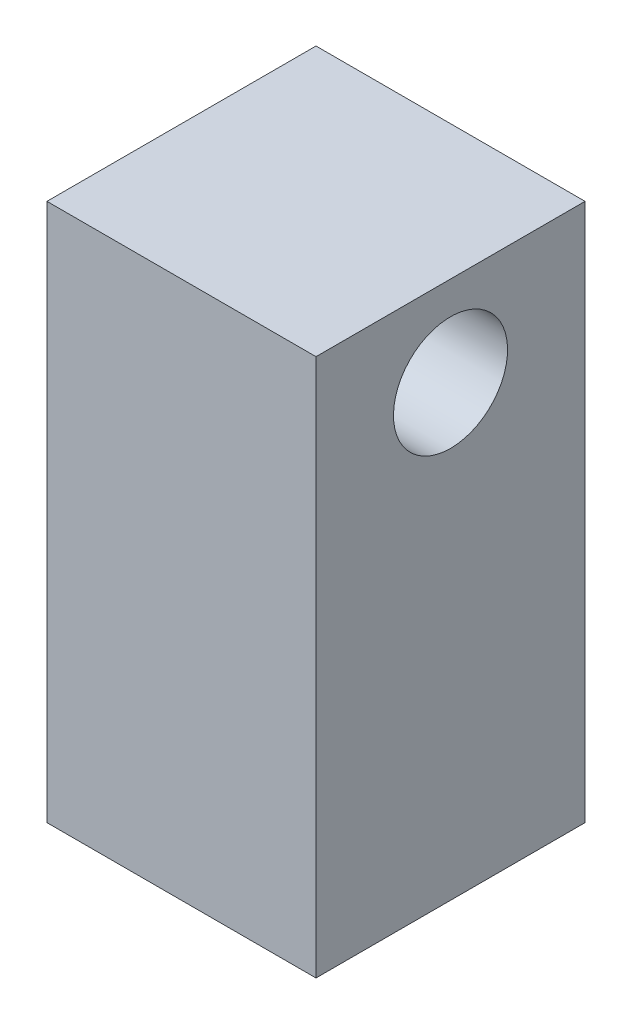
SolidWorks part; units mm, degrees
ref_plane "Front Plane" through (0, 0, 0) normal (0, 0, 1) x (1, 0, 0)
ref_plane "Top Plane" through (0, 0, 0) normal (0, 1, 0) x (1, 0, 0)
ref_plane "Right Plane" through (0, 0, 0) normal (1, 0, 0) x (0, 0, -1)
sketch "Sketch1" plane through (0, 0, 0) normal (0, 0, 1) x (1, 0, 0)
  line L1 (-4.7625, 9.525) -> (4.7625, 9.525)
  line L2 (-4.7625, 9.525) -> (-4.7625, -9.525)
  line L3 (-4.7625, -9.525) -> (4.7625, -9.525)
  line L4 (4.7625, 9.525) -> (4.7625, -9.525)
  line L5 (-4.7625, 9.525) -> (4.7625, -9.525) construction
  line L6 (-4.7625, -9.525) -> (4.7625, 9.525) construction
  point P0 (0, 0)
  dimension "D1" = 19.05
  dimension "D2" = 9.525
extrude "Boss-Extrude1" add sketch "Sketch1" along normal blind 9.525
sketch "Sketch2" plane through (0, -9.525, 0) normal (0, -1, 0) x (1, 0, 0)
  line L0 (-4.7625, 0) -> (4.7625, 0) construction
  line L1 (4.7625, 9.525) -> (4.7625, 0) construction
  circle A0 centre (0, 4.7625) radius 1.2891
  point P4 (0, 0)
  point P7 (4.7625, 4.7625)
  dimension "D1" = 2.5781
extrude "Cut-Extrude1" cut sketch "Sketch2" against normal blind 12.7
sketch "Sketch4" plane through (-4.7625, 0, 0) normal (-1, 0, 0) x (0, 0, 1)
  line L0 (9.525, 9.525) -> (0, 9.525) construction
  circle A0 centre (4.7625, 6.35) radius 2.0193
  point P4 (4.7625, 9.525)
  dimension "D1" = 4.0386
  dimension "D2" = 3.175
extrude "Cut-Extrude2" cut sketch "Sketch4" against normal through all
